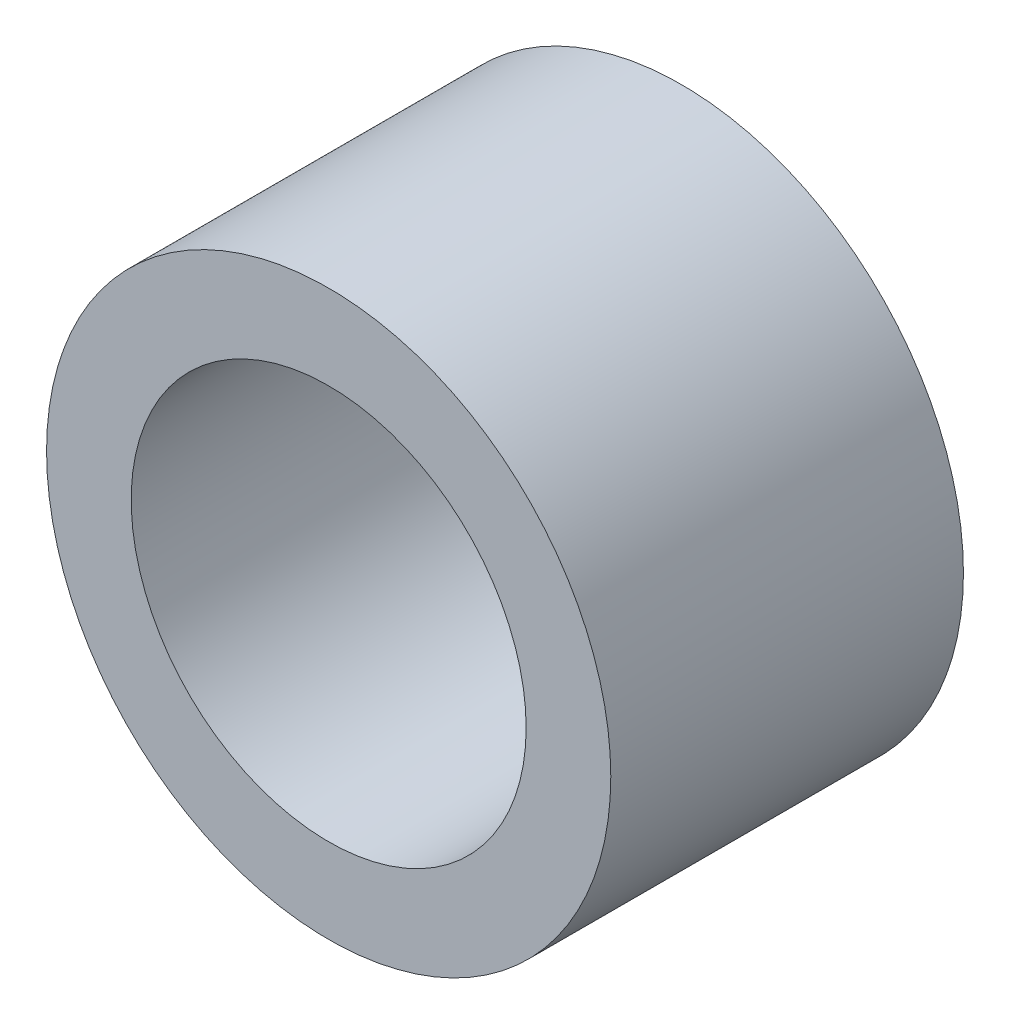
SolidWorks part; units mm, degrees
ref_plane "Front" through (0, 0, 0) normal (0, 0, 1) x (1, 0, 0)
ref_plane "Top" through (0, 0, 0) normal (0, 1, 0) x (1, 0, 0)
ref_plane "Right" through (0, 0, 0) normal (1, 0, 0) x (0, 0, -1)
sketch "Sketch1" plane through (0, 0, 0) normal (0, 0, 1) x (1, 0, 0)
  circle A0 centre (0, 0) radius 5.08
  circle A1 centre (0, 0) radius 3.556
  dimension "D1" = 10.16
  dimension "D2" = 7.112
extrude "Boss-Extrude1" add sketch "Sketch1" along normal mid plane 6.35
